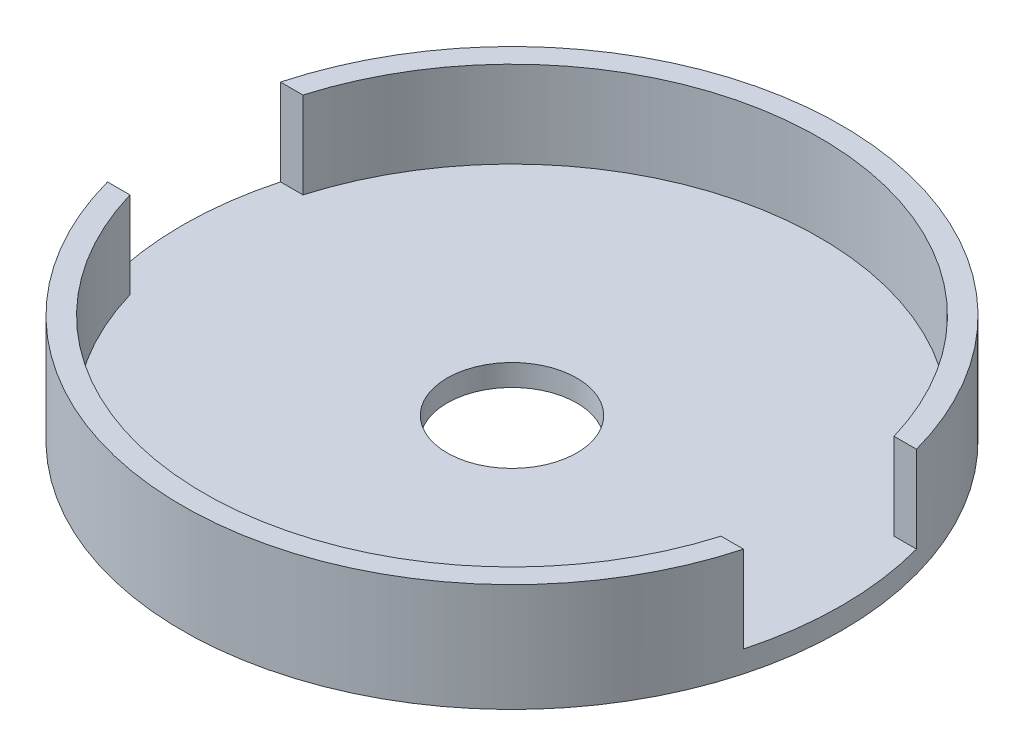
SolidWorks part; units mm, degrees
material "ABS"
ref_plane "Front Plane" through (0, 0, 0) normal (0, 0, 1) x (1, 0, 0)
ref_plane "Top Plane" through (0, 0, 0) normal (0, 1, 0) x (1, 0, 0)
ref_plane "Right Plane" through (0, 0, 0) normal (1, 0, 0) x (0, 0, -1)
sketch "Sketch1" plane through (0, 0, 0) normal (0, 0, 1) x (1, 0, 0)
  line L0 (0, 0) -> (-76.2, 0)
  line L1 (-76.2, 0) -> (-76.2, 25)
  line L2 (-76.2, 25) -> (-71.2, 25)
  line L3 (-71.2, 25) -> (-71.2, 5)
  line L4 (-71.2, 5) -> (0, 5)
  line L5 (0, 5) -> (0, 0)
  dimension "D1" = 5
  dimension "D2" = 76.2
  dimension "D3" = 25
  dimension "D4" = 5
revolve "Revolve1" add sketch "Sketch1" angle 360 about L5
sketch "Sketch2" plane through (0, 0, 0) normal (1, 0, 0) x (0, 0, -1)
  line L0 (76.2, 25) -> (-76.2, 25) construction
  line L1 (-20, 25) -> (20, 25)
  line L2 (-20, 25) -> (-20, 5)
  line L3 (-20, 5) -> (20, 5)
  line L4 (20, 25) -> (20, 5)
  point P6 (0, 25)
  dimension "D1" = 5
  dimension "D2" = 40
extrude "Cut-Extrude2" cut sketch "Sketch2" against normal through all both and the other way through all
sketch "Sketch3" plane through (0, 5, 0) normal (0, 1, 0) x (1, 0, 0)
  circle A0 centre (0, 0) radius 15
  dimension "D1" = 30
extrude "Cut-Extrude3" cut sketch "Sketch3" against normal through all both and the other way through all
